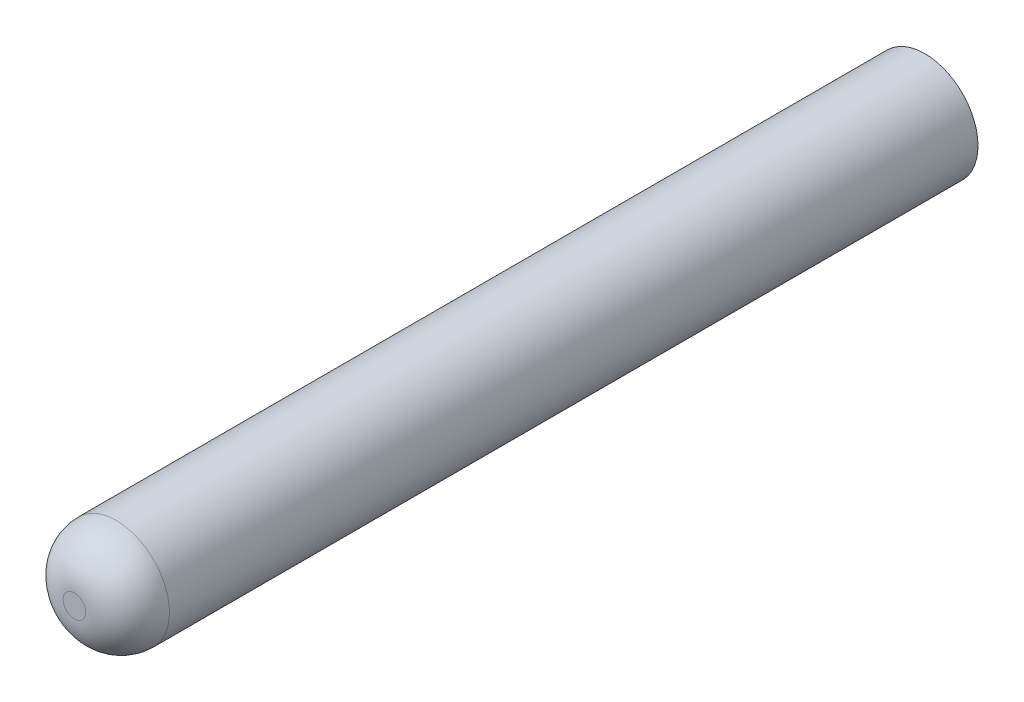
SolidWorks part; units mm, degrees
ref_plane "Front Plane" through (0, 0, 0) normal (0, 0, 1) x (1, 0, 0)
ref_plane "Top Plane" through (0, 0, 0) normal (0, 1, 0) x (1, 0, 0)
ref_plane "Right Plane" through (0, 0, 0) normal (1, 0, 0) x (0, 0, -1)
sketch "Sketch2" plane through (0, 0, 0) normal (0, 0, 1) x (1, 0, 0)
  circle A0 centre (0, 0) radius 12.7
  dimension "D1" = 25.4
extrude "Boss-Extrude1" add sketch "Sketch2" along normal blind 203.2
fillet "Fillet1" radius 10 1 edges at (12.7, 0, 203.2)
